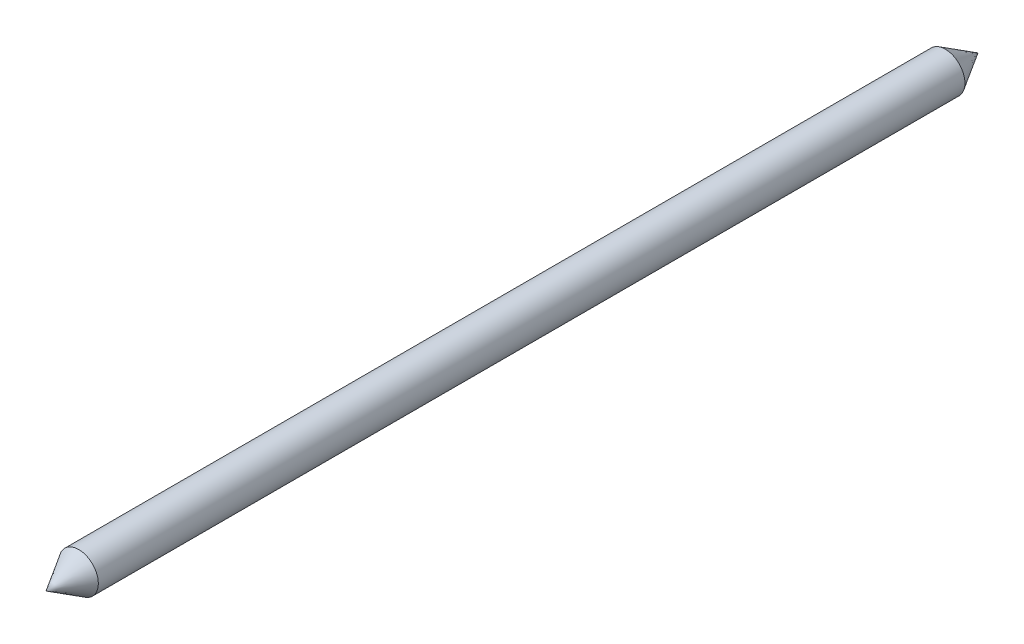
SolidWorks part; units mm, degrees
ref_plane "Front Plane" through (0, 0, 0) normal (0, 0, 1) x (1, 0, 0)
ref_plane "Top Plane" through (0, 0, 0) normal (0, 1, 0) x (1, 0, 0)
ref_plane "Right Plane" through (0, 0, 0) normal (1, 0, 0) x (0, 0, -1)
sketch "Sketch2" plane through (0, 0, 0) normal (0, 1, 0) x (1, 0, 0)
  line L0 (7.62, 168.275) -> (7.62, -168.275)
  line L1 (7.62, -168.275) -> (0, -180.975)
  line L2 (0, -180.975) -> (0, 180.975)
  line L3 (0, 180.975) -> (7.62, 168.275)
  point P2 (0, 0)
  dimension "D1" = 12.7
  dimension "D2" = 12.7
  dimension "D3" = 361.95
  dimension "D4" = 7.62
revolve "Revolve1" add sketch "Sketch2" angle 360 about L2
